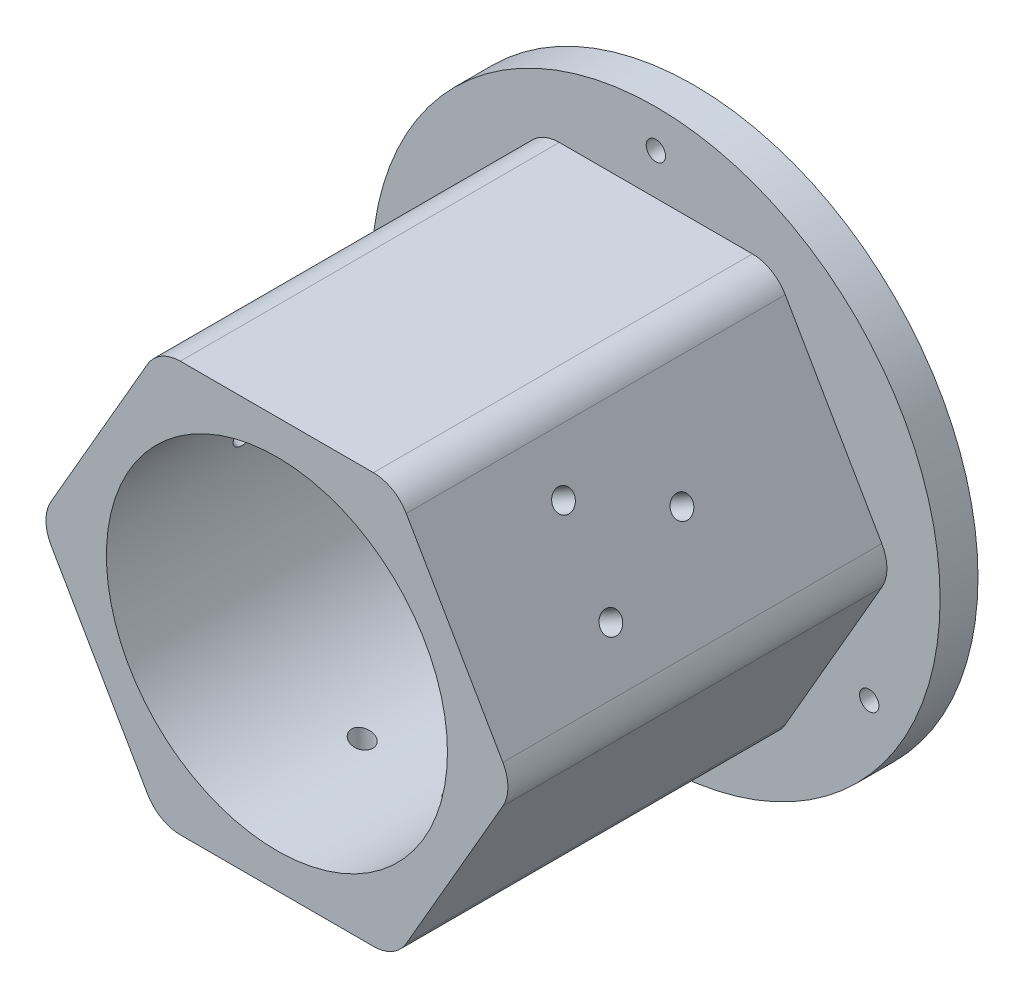
SolidWorks part; units mm, degrees
material "ABS PC"
ref_plane "Front Plane" through (0, 0, 0) normal (0, 0, 1) x (1, 0, 0)
ref_plane "Top Plane" through (0, 0, 0) normal (0, 1, 0) x (1, 0, 0)
ref_plane "Right Plane" through (0, 0, 0) normal (1, 0, 0) x (0, 0, -1)
sketch "Sketch1" plane through (0, 0, 0) normal (0, 0, 1) x (1, 0, 0)
  circle A0 centre (0, 0) radius 75
  dimension "D1" = 150
extrude "Boss-Extrude1" add sketch "Sketch1" along normal blind 10
sketch "Sketch2" plane through (0, 0, 10) normal (0, 0, 1) x (1, 0, 0)
  line L1 (59.6132, 5) -> (34.1368, 49.1266)
  line L2 (25.4765, 54.1266) -> (-25.4765, 54.1266)
  line L3 (-34.1368, 49.1266) -> (-59.6132, 5)
  line L4 (-59.6132, -5) -> (-34.1368, -49.1266)
  line L5 (-25.4765, -54.1266) -> (25.4765, -54.1266)
  line L6 (34.1368, -49.1266) -> (59.6132, -5)
  circle A0 centre (0, 0) radius 62.5 construction
  arc A1 (25.4765, -54.1266) -> (34.1368, -49.1266) centre (25.4765, -44.1266) ccw
  arc A2 (-34.1368, -49.1266) -> (-25.4765, -54.1266) centre (-25.4765, -44.1266) ccw
  arc A3 (-59.6132, -5) -> (-59.6132, 5) centre (-50.953, 0) cw
  arc A4 (-25.4765, 54.1266) -> (-34.1368, 49.1266) centre (-25.4765, 44.1266) ccw
  arc A5 (34.1368, 49.1266) -> (25.4765, 54.1266) centre (25.4765, 44.1266) ccw
  arc A6 (59.6132, -5) -> (59.6132, 5) centre (50.953, 0) ccw
  point P11 (31.25, -54.1266)
  dimension "D1" = 10
  dimension "D2" = 10
extrude "Boss-Extrude2" add sketch "Sketch2" along normal blind 100
sketch "Sketch4" plane through (0, 0, 110) normal (0, 0, 1) x (1, 0, 0)
  circle A0 centre (0, 0) radius 45
extrude "Cut-Extrude1" cut sketch "Sketch4" against normal up to surface (100 mm away) up to face at (0, 0, 10)
sketch "Sketch5" plane through (0, -54.1266, 0) normal (0, -1, 0) x (1, 0, 0)
  circle A0 centre (0, 50) radius 2.8
  circle A1 centre (-12.5, 75) radius 2.8
  circle A2 centre (12.5, 75) radius 2.8
  point P6 (0, 0)
  point P7 (0, 0)
  dimension "D1" = 25
  dimension "D5" = 5.6
  dimension "D6" = 5.6
  dimension "D7" = 5.6
  dimension "D2" = 25
  dimension "D3" = 12.5
  dimension "D4" = 0
  dimension "D8" = 50
  dimension "D9" = 12.5
extrude "Cut-Extrude2" cut sketch "Sketch5" against normal up to surface (9.2138 mm away)
pattern_circular "CirPattern1" count 3 every 120 about axis through (0, 0, -117.2792) along (0, 0, 1) of "Cut-Extrude2"
sketch "Sketch7" plane through (0, 0, 10) normal (0, 0, 1) x (1, 0, 0)
  circle A0 centre (0, 65) radius 2.55
  circle A1 centre (56.2917, -32.5) radius 2.55
  circle A2 centre (-56.2917, -32.5) radius 2.55
  point P9 (0, 0)
  dimension "D1" = 65
  dimension "D4" = 5.1
  dimension "D2" = 0
  dimension "D3" = 3
extrude "Cut-Extrude3" cut sketch "Sketch7" against normal up to surface (10 mm away) up to face at (75, 0, 0)
